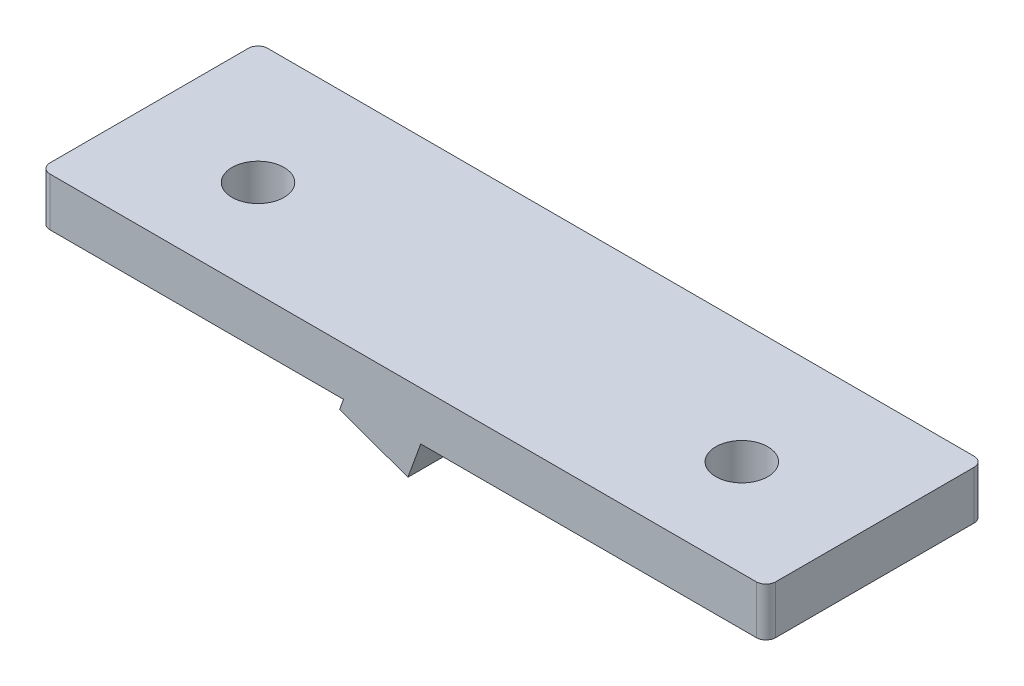
SolidWorks part; units mm, degrees
ref_plane "前视基准面" through (0, 0, 0) normal (0, 0, 1) x (1, 0, 0)
ref_plane "上视基准面" through (0, 0, 0) normal (0, 1, 0) x (1, 0, 0)
ref_plane "右视基准面" through (0, 0, 0) normal (1, 0, 0) x (0, 0, -1)
other "Configuration Table"
sketch "草图1" plane through (0, 0, 0) normal (0, 1, 0) x (1, 0, 0)
  line L1 (-30, 18) -> (30, 18)
  line L2 (-30, 18) -> (-30, 0)
  line L3 (-30, 0) -> (30, 0)
  line L4 (30, 18) -> (30, 0)
  line L5 (-30, 18) -> (30, 0) construction
  line L6 (-30, 0) -> (30, 18) construction
  circle A0 centre (-20, 8) radius 2.15
  circle A1 centre (20, 8) radius 2.15
  point P4 (0, 9)
  dimension "D3" = 4.3
  dimension "D4" = 4.3
  dimension "D1" = 60
  dimension "D2" = 18
  dimension "D5" = 20
  dimension "D6" = 8
  dimension "D7" = 8
  dimension "D8" = 20
extrude "凸台-拉伸1" add sketch "草图1" along normal blind 4
ref_plane "基准面1" through (0, -23, 0) normal (0, -1, 0) x (-1, 0, 0)
sketch "草图2" plane through (0, -23, 0) normal (0, -1, 0) x (-1, 0, 0)
  point P0 (0, 0)
sketch "草图3" plane through (0, 0, 0) normal (0, -1, 0) x (1, 0, 0)
  line L0 (4, 0) -> (4, -18) construction
  dimension "D1" = 4
ref_plane "基准面2" through (0.4679, 1.2856, 0) normal (0.342, 0.9397, 0) x (0, 0, -1)
sketch "草图5" plane through (0, 0, -18) normal (0, 0, -1) x (-1, 0, 0)
  line L0 (-19.3323, 0) -> (10.039, 0)
  line L1 (-30, 0) -> (30, 0) construction
  line L3 (-19.3323, 0) -> (-15.5545, -10.3794)
  line L4 (10.039, 0) -> (10.381, -0.9397)
  line L5 (-15.5545, -10.3794) -> (10.381, -0.9397)
  dimension "D1" = 10.3
  dimension "D2" = 17.3
  dimension "D3" = 1
extrude "凸台-拉伸3" add sketch "草图5" against normal blind 2.2
sketch "草图6" plane through (0, 0, -18) normal (0, 0, -1) x (-1, 0, 0)
  line L0 (-16.3652, -8.7371) -> (-9.8668, -26.5912)
  line L1 (0, 0) -> (35.5322, 0) construction
  line L2 (16.4446, -17.0146) -> (-9.8668, -26.5912)
  line L3 (9.9462, 0.8395) -> (16.4446, -17.0146)
  line L4 (-16.3652, -8.7371) -> (9.9462, 0.8395)
  dimension "D1" = 17.5
  dimension "D2" = 19
  dimension "D3" = 10.5
  dimension "D4" = 20
extrude "切除-拉伸1" cut sketch "草图6" against normal blind 2.5
sketch "草图4" plane through (0.4679, 1.2856, 0) normal (0.342, 0.9397, 0) x (0, 0, -1)
  line L0 (0, 29.5589) -> (0, -26.8227) construction
  line L1 (0, 4.6335) -> (4, 4.6335)
  line L2 (18, -26.8227) -> (18, 29.5589) construction
  line L3 (0, -1.3665) -> (4, -1.3665)
  line L4 (0, 4.6335) -> (0, -1.3665)
  line L5 (18, 4.6335) -> (18, -1.3665)
  line L6 (12, 4.6335) -> (18, 4.6335)
  line L7 (12, -1.3665) -> (18, -1.3665)
  arc A0 (4, -1.3665) -> (12, -1.3665) centre (8, 1.6335) ccw
  arc A1 (12, 4.6335) -> (4, 4.6335) centre (8, 1.6335) ccw
  dimension "D1" = 10
  dimension "D2" = 9.5
  dimension "D3" = 8
  dimension "D4" = 3
  dimension "D5" = 3
extrude "凸台-拉伸2" add sketch "草图4" against normal up to surface (3.981 mm away) up to face at (-0.4696, -2.6097, -16.4333)
fillet "圆角1" radius 0.8 4 edges at (-30, 2, -18) (-30, 2, 0) (30, 2, 0) (30, 2, -18)
